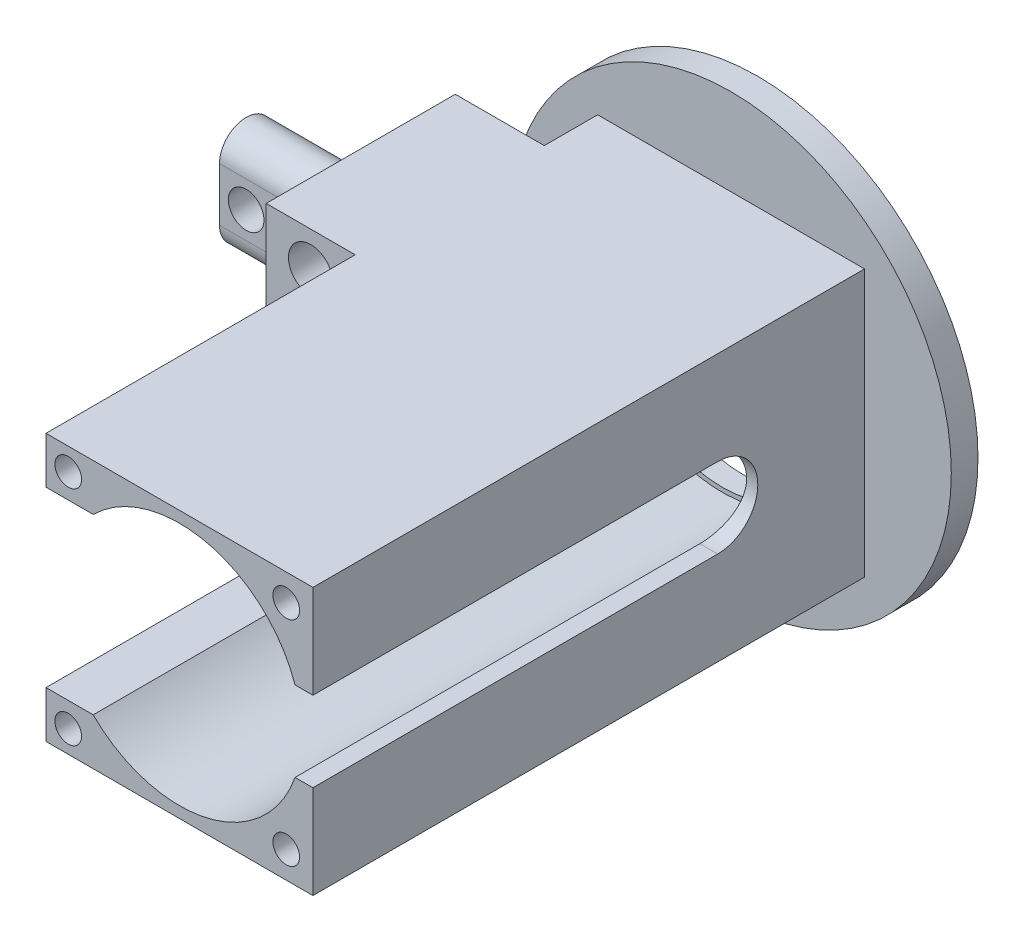
SolidWorks part; units mm, degrees
ref_plane "Ebene vorne" through (0, 0, 0) normal (0, 0, 1) x (1, 0, 0)
ref_plane "Ebene oben" through (0, 0, 0) normal (0, 1, 0) x (1, 0, 0)
ref_plane "Ebene rechts" through (0, 0, 0) normal (1, 0, 0) x (0, 0, -1)
sketch "Sketch1" plane through (0, 0, 0) normal (0, 0, 1) x (1, 0, 0)
  line L1 (-15, 15) -> (15, 15)
  line L2 (-15, 15) -> (-15, -15)
  line L3 (-15, -15) -> (15, -15)
  line L4 (15, 15) -> (15, -15)
  line L5 (0, -15) -> (0, 15) construction
  line L6 (-15, 0) -> (15, 0) construction
  point P0 (0, 0)
  dimension "D1" = 30
  dimension "D2" = 30
extrude "Boss-Extrude1" add sketch "Sketch1" along normal blind 65
sketch "Sketch2" plane through (0, 0, 0) normal (0, 0, -1) x (-1, 0, 0)
  circle A0 centre (0, 0) radius 24.75
  dimension "D1" = 49.5
extrude "Boss-Extrude2" add sketch "Sketch2" against normal blind 3
sketch "Sketch3" plane through (0, 0, 0) normal (0, 0, -1) x (-1, 0, 0)
  circle A0 centre (0, 0) radius 23.75
  circle A1 centre (0, 0) radius 24.75 construction
  dimension "D1" = 1
extrude "Cut-Extrude1" cut sketch "Sketch3" against normal blind 1.6
sketch "Sketch4" plane through (0, 0, 1.6) normal (0, 0, -1) x (-1, 0, 0)
  circle A0 centre (0, 0) radius 13.25
  dimension "D1" = 26.5
extrude "Cut-Extrude4" cut sketch "Sketch4" against normal up to next
sketch "Sketch5" plane through (0, 0, 65) normal (0, 0, 1) x (1, 0, 0)
  circle A0 centre (0, 0) radius 13.75
  dimension "D1" = 27.5
extrude "Cut-Extrude5" cut sketch "Sketch5" against normal blind 61
sketch "Sketch6" plane through (15, 0, 0) normal (1, 0, 0) x (0, 0, -1)
  line L0 (-19.5, 0) -> (-65, 0) construction
  line L1 (-19.5, -4.5) -> (-65, -4.5)
  line L2 (-19.5, 4.5) -> (-65, 4.5)
  line L4 (-3, 15) -> (-3, -15) construction
  line L5 (-65, -15) -> (-65, 15) construction
  arc A0 (-19.5, -4.5) -> (-19.5, 4.5) centre (-19.5, 0) ccw
  arc A1 (-65, 4.5) -> (-65, -4.5) centre (-65, 0) ccw
  point P3 (-42.25, 0)
  dimension "D1" = 4.5
  dimension "D2" = 16.5
  dimension "D3" = 0
extrude "Cut-Extrude9" cut sketch "Sketch6" against normal up to next
sketch "Sketch8" plane through (-15, 0, 0) normal (-1, 0, 0) x (0, 0, 1)
  line L0 (4, -13.75) -> (4, 13.75) construction
  line L1 (19, 10) -> (9, 10)
  line L2 (19, 10) -> (19, -10)
  line L3 (19, -10) -> (9, -10)
  line L4 (9, 10) -> (9, -10)
  line L5 (14, -10) -> (14, 10) construction
  line L6 (19, 0) -> (9, 0) construction
  line L7 (65, -15) -> (3, -15) construction
  point P0 (14, 0)
  dimension "D1" = 5
  dimension "D2" = 20
  dimension "D3" = 10
  dimension "D4" = 5
extrude "Boss-Extrude3" add sketch "Sketch8" along normal blind 10
sketch "Sketch9" plane through (-25, 0, 0) normal (-1, 0, 0) x (0, 0, 1)
  line L0 (14, 3) -> (14, -3) construction
  line L1 (17, 3) -> (17, -3)
  line L2 (11, 3) -> (11, -3)
  line L3 (19, -10) -> (19, 10) construction
  line L4 (19, 10) -> (9, 10) construction
  arc A0 (17, 3) -> (11, 3) centre (14, 3) ccw
  arc A1 (11, -3) -> (17, -3) centre (14, -3) ccw
  point P2 (14, 0)
  dimension "D4" = 3
  dimension "D1" = 6
  dimension "D2" = 5
  dimension "D3" = 10
extrude "Boss-Extrude4" add sketch "Sketch9" along normal blind 18.5
sketch "Sketch10" plane through (0, 0, 17) normal (0, 0, 1) x (1, 0, 0)
  line L0 (-43.5, -3) -> (-43.5, 3) construction
  circle A0 centre (-40.5, 0) radius 2
  circle A1 centre (-32, 0) radius 2
  dimension "D1" = 4
  dimension "D2" = 4
  dimension "D3" = 3
  dimension "D4" = 11.5
extrude "Cut-Extrude10" cut sketch "Sketch10" against normal up to next
sketch "Sketch11" plane through (-15, 0, 0) normal (-1, 0, 0) x (0, 0, 1)
  line L0 (40, 0) -> (65, 0) construction
  line L1 (40, 9.75) -> (65, 9.75)
  line L2 (40, -9.75) -> (65, -9.75)
  line L3 (4, -13.75) -> (4, 13.75) construction
  line L4 (65, 15) -> (65, -15) construction
  arc A0 (40, 9.75) -> (40, -9.75) centre (40, 0) ccw
  arc A1 (65, -9.75) -> (65, 9.75) centre (65, 0) ccw
  point P3 (52.5, 0)
  dimension "D1" = 9.75
  dimension "D2" = 36
  dimension "D3" = 0
extrude "Cut-Extrude11" cut sketch "Sketch11" against normal up to next
sketch "Sketch13" plane through (0, 0, 3) normal (0, 0, 1) x (1, 0, 0)
  line L0 (15, -15) -> (-15, -15) construction
  line L1 (-7.5, -15) -> (7.5, -15)
  line L2 (-7.5, -15) -> (-7.5, -22)
  line L3 (-7.5, -22) -> (7.5, -22)
  line L4 (7.5, -15) -> (7.5, -22)
  line L5 (0, -22) -> (0, -15) construction
  line L6 (-7.5, -18.5) -> (7.5, -18.5) construction
  point P0 (0, -18.5)
  dimension "D1" = 15
  dimension "D2" = 7
  dimension "D3" = 0
  dimension "D4" = 7.5
extrude "Cut-Extrude12" cut sketch "Sketch13" against normal up to next
sketch "Sketch14" plane through (-15, 0, 0) normal (-1, 0, 0) x (0, 0, 1)
  line L0 (19, -10) -> (19, 10) construction
  line L1 (19, 10) -> (30.25, 10)
  line L2 (19, 10) -> (19, -10)
  line L3 (19, -10) -> (30.25, -10)
  line L4 (30.25, 10) -> (30.25, -10)
  line L5 (24.625, -10) -> (24.625, 10) construction
  line L6 (19, 0) -> (30.25, 0) construction
  arc A0 (40, 9.75) -> (40, -9.75) centre (40, 0) ccw construction
  point P0 (24.625, 0)
  point P7 (30.25, 0)
  dimension "D1" = 0
  dimension "D2" = 0
  dimension "D3" = 0
  dimension "D4" = 0
extrude "Boss-Extrude5" add sketch "Sketch14" along normal blind 10
sketch "Sketch15" plane through (-15, 0, 0) normal (-1, 0, 0) x (0, 0, 1)
  line L0 (65, 15) -> (3, 15) construction
  line L1 (9, 15) -> (30.25, 15)
  line L2 (9, 15) -> (9, 10)
  line L3 (9, 10) -> (30.25, 10)
  line L4 (30.25, 15) -> (30.25, 10)
  line L5 (19.625, 10) -> (19.625, 15) construction
  line L6 (9, 12.5) -> (30.25, 12.5) construction
  line L7 (30.25, 10) -> (9, 10) construction
  point P0 (19.625, 12.5)
  dimension "D1" = 0
  dimension "D2" = 0
  dimension "D3" = 0
  dimension "D4" = 0
extrude "Boss-Extrude6" add sketch "Sketch15" along normal blind 10
sketch "Sketch16" plane through (0, -10, 0) normal (0, -1, 0) x (-1, 0, 0)
  line L0 (25, -30.25) -> (15, -30.25) construction
  line L1 (25, -30.25) -> (15, -30.25)
  line L2 (25, -30.25) -> (25, -9)
  line L3 (25, -9) -> (15, -9)
  line L4 (15, -30.25) -> (15, -9)
  line L5 (20, -9) -> (20, -30.25) construction
  line L6 (25, -19.625) -> (15, -19.625) construction
  line L7 (25, -9) -> (25, -30.25) construction
  line L8 (25, -9) -> (15, -9) construction
  line L9 (15, -9) -> (15, -30.25) construction
  point P0 (20, -19.625)
  dimension "D1" = 0
  dimension "D2" = 0
  dimension "D3" = 0
  dimension "D4" = 0
extrude "Boss-Extrude7" add sketch "Sketch16" along normal blind 5
sketch "Sketch18" plane through (0, 0, 30.25) normal (0, 0, 1) x (1, 0, 0)
  line L0 (-15, -15) -> (-25, -15) construction
  line L1 (-25, 15) -> (-15, 15) construction
  line L2 (-25, -15) -> (-25, 15) construction
  circle A0 centre (-20, -11) radius 2.5
  circle A1 centre (-20, 11) radius 2.5
  dimension "D2" = 5
  dimension "D3" = 5
  dimension "D1" = 0
  dimension "D4" = 4
  dimension "D5" = 4
  dimension "D6" = 5
extrude "Cut-Extrude13" cut sketch "Sketch18" against normal blind 5.5
sketch "Sketch19" plane through (0, 0, 65) normal (0, 0, 1) x (1, 0, 0)
  line L0 (15, 15) -> (-15, 15) construction
  line L1 (-15, -15) -> (15, -15) construction
  line L2 (15, -15) -> (15, -4.5) construction
  line L3 (15, 4.5) -> (15, 15) construction
  line L4 (-15, 15) -> (-15, 9.75) construction
  line L5 (-15, -9.75) -> (-15, -15) construction
  circle A0 centre (12, -12) radius 1.5
  circle A1 centre (12, 12) radius 1.5
  circle A2 centre (-12.5, -12.5) radius 1.5
  circle A3 centre (-12.5, 12.5) radius 1.5
  point P18 (0, 0)
  dimension "D1" = 3
  dimension "D2" = 3
  dimension "D7" = 3
  dimension "D8" = 3
  dimension "D3" = 3
  dimension "D4" = 3
  dimension "D5" = 3
  dimension "D6" = 3
  dimension "D9" = 2.5
  dimension "D10" = 2.5
  dimension "D11" = 2.5
  dimension "D12" = 2.5
extrude "Cut-Extrude14" cut sketch "Sketch19" against normal blind 3.5
sketch "Sketch20" plane through (-25, 0, 0) normal (-1, 0, 0) x (0, 0, 1)
  line L0 (30.25, -15) -> (9, -15) construction
  line L1 (30.25, 15) -> (9, 15) construction
  line L2 (9, 15) -> (9, -15) construction
  circle A0 centre (14, 11) radius 1.5
  circle A1 centre (14, -11) radius 1.5
  dimension "D2" = 3
  dimension "D3" = 3
  dimension "D1" = 0
  dimension "D4" = 4
  dimension "D5" = 4
  dimension "D6" = 5
extrude "Cut-Extrude15" cut sketch "Sketch20" against normal blind 3.5
